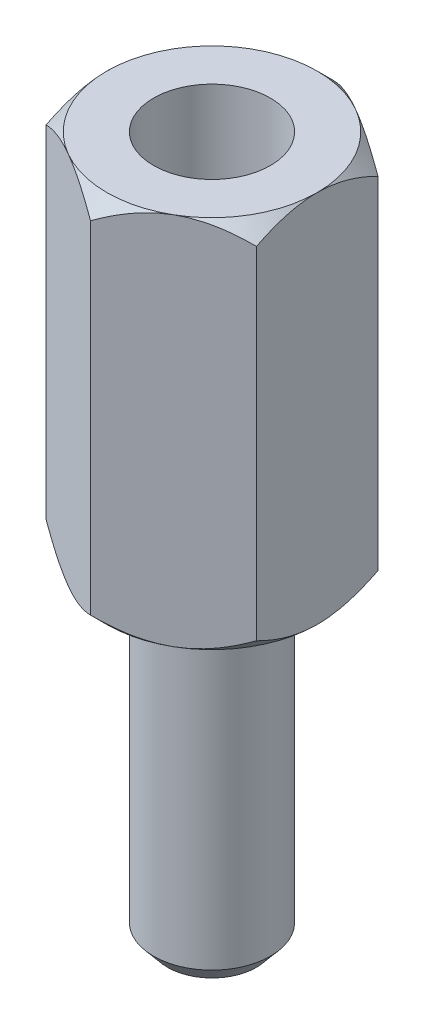
SolidWorks part; units mm, degrees
ref_plane "Front Plane" through (0, 0, 0) normal (0, 0, 1) x (1, 0, 0)
ref_plane "Top Plane" through (0, 0, 0) normal (0, 1, 0) x (1, 0, 0)
ref_plane "Right Plane" through (0, 0, 0) normal (1, 0, 0) x (0, 0, -1)
sketch "Sketch1" plane through (0, 0, 0) normal (0, 1, 0) x (1, 0, 0)
  circle A0 centre (0, 0) radius 1.25
  dimension "D1" = 2.5
extrude "Boss-Extrude1" add sketch "Sketch1" along normal blind 7
sketch "Sketch2" plane through (0, 7, 0) normal (0, 1, 0) x (1, 0, 0)
  line L1 (0, 2.5981) -> (-2.25, 1.299)
  line L2 (-2.25, 1.299) -> (-2.25, -1.299)
  line L3 (-2.25, -1.299) -> (0, -2.5981)
  line L4 (0, -2.5981) -> (2.25, -1.299)
  line L5 (2.25, -1.299) -> (2.25, 1.299)
  line L6 (2.25, 1.299) -> (0, 2.5981)
  circle A0 centre (0, 0) radius 2.25 construction
  dimension "D1" = 4.5
extrude "Boss-Extrude2" add sketch "Sketch2" along normal blind 8
sketch "Sketch3" plane through (0, 15, 0) normal (0, 1, 0) x (1, 0, 0)
  circle A0 centre (0, 0) radius 1.25
  dimension "D1" = 2.5
extrude "Cut-Extrude1" cut sketch "Sketch3" against normal blind 4.8
sketch "Sketch4" plane through (0, 15, 0) normal (0, 1, 0) x (1, 0, 0)
  circle A0 centre (0, 0) radius 2.25
extrude "Cut-Extrude2" cut sketch "Sketch4" against normal through all draft 45 flip side to cut
sketch "Sketch5" plane through (0, 7, 0) normal (0, -1, 0) x (1, 0, 0)
  circle A0 centre (0, 0) radius 2.25
extrude "Cut-Extrude3" cut sketch "Sketch5" against normal through all draft 45 flip side to cut
chamfer "Chamfer1" distance 0.3 angle 50 1 edges at (0, 0, 1.25)
